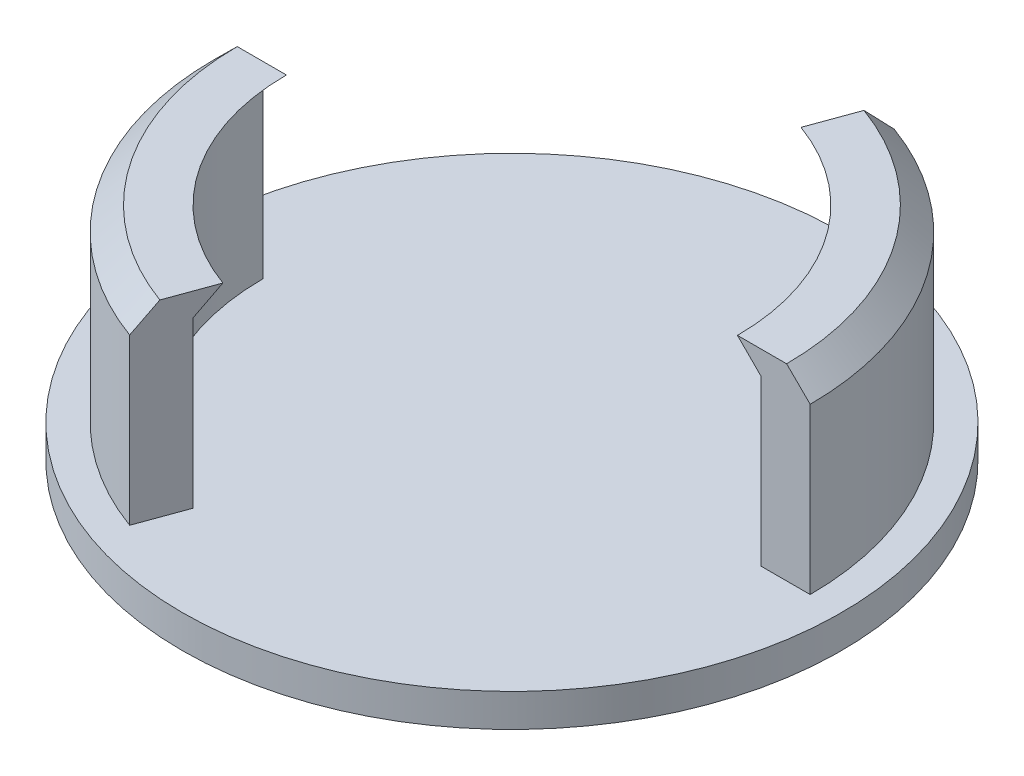
SolidWorks part; units mm, degrees
ref_plane "Front Plane" through (0, 0, 0) normal (0, 0, 1) x (1, 0, 0)
ref_plane "Top Plane" through (0, 0, 0) normal (0, 1, 0) x (1, 0, 0)
ref_plane "Right Plane" through (0, 0, 0) normal (1, 0, 0) x (0, 0, -1)
sketch "Sketch1" plane through (0, 0, 0) normal (0, 1, 0) x (1, 0, 0)
  circle A0 centre (0, 0) radius 20
  dimension "D1" = 40
extrude "Boss-Extrude1" add sketch "Sketch1" along normal blind 2
sketch "Sketch2" plane through (0, 0, 0) normal (0, 0, 1) x (1, 0, 0)
  line L0 (0, 0) -> (0, 2)
  line L1 (20, 2) -> (-20, 2) construction
  line L2 (-15.1, 2) -> (15.1, 2)
  line L3 (15.1, 2) -> (15.1, 12)
  line L4 (15.1, 12) -> (13.6858, 13.4142)
  line L5 (15.1, 2) -> (18.1, 2)
  line L6 (18.1, 2) -> (18.1, 12)
  line L7 (18.1, 12) -> (16.6699, 13.4142)
  line L8 (16.6699, 13.4142) -> (13.6858, 13.4142)
  line L9 (-15.1, 2) -> (-18.1, 2)
  line L10 (-18.1, 2) -> (-18.1, 12)
  line L11 (-15.1, 2) -> (-15.1, 12)
  line L12 (-16.6699, 13.4142) -> (-13.6858, 13.4142)
  line L13 (-18.1, 12) -> (-16.6699, 13.4142)
  line L14 (-15.1, 12) -> (-13.6858, 13.4142)
  dimension "D1" = 15.1
  dimension "D2" = 10
  dimension "D3" = 2
  dimension "D4" = 3
revolve "Revolve1" add sketch "Sketch2" angle 70 about L0
